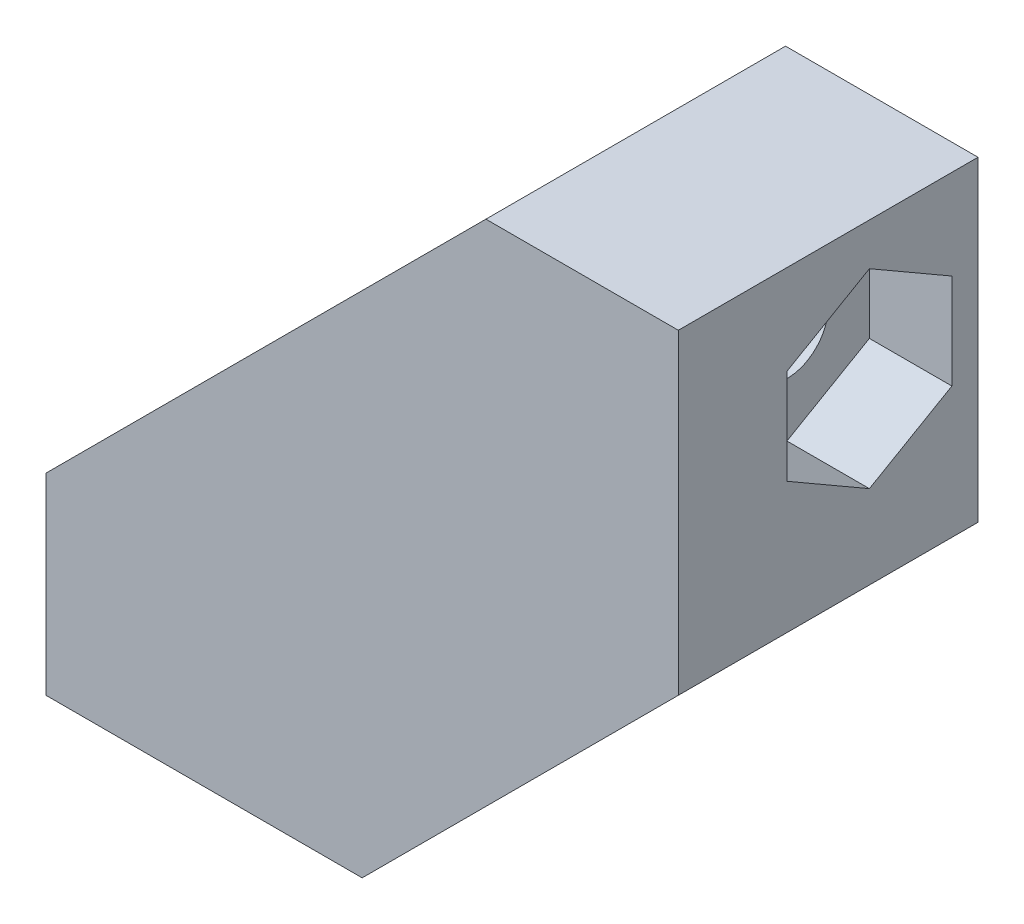
SolidWorks part; units mm, degrees
ref_plane "Front Plane" through (0, 0, 0) normal (0, 0, 1) x (1, 0, 0)
ref_plane "Top Plane" through (0, 0, 0) normal (0, 1, 0) x (1, 0, 0)
ref_plane "Right Plane" through (0, 0, 0) normal (1, 0, 0) x (0, 0, -1)
sketch "Sketch1" plane through (0, 0, 0) normal (0, 0, 1) x (1, 0, 0)
  line L0 (30, 0) -> (30, 6) construction
  line L2 (30, 0) -> (30, 8)
  line L3 (30, 8) -> (38, 8)
  line L5 (27, 0) -> (27, 6) construction
  line L6 (30, 0) -> (22, 0)
  line L8 (45, -7) -> (22, -7)
  line L9 (22, 0) -> (22, -7)
  line L11 (38, 8) -> (38, 16)
  line L12 (38, 16) -> (45, 16)
  line L13 (45, -7) -> (45, 16)
  line L14 (30, 6) -> (0, 6) construction
  line L15 (0, 0) -> (30, 0) construction
  line L16 (33.5, -7) -> (45, 4.5)
  dimension "D1" = 7
  dimension "D2" = 5
extrude "Boss-Extrude1" add sketch "Sketch1" against normal up to surface (7.9 mm away) contours L8 L16 L13 L12 L11 L3 L2 L6 L9
sketch "Sketch2" plane through (0, -7, 0) normal (0, -1, 0) x (1, 0, 0)
  circle A0 centre (27, -3.95) radius 1.5
  circle A1 centre (27, -3.95) radius 1.5 construction
extrude "Cut-Extrude1" cut sketch "Sketch2" against normal through all
sketch "Sketch3" plane through (38, -7, 0) normal (0, 1, 0) x (0, 0, -1)
  line L0 (0.95, 12.7321) -> (3.95, 14.4641)
  line L1 (3.95, 14.4641) -> (6.95, 12.7321)
  line L2 (6.95, 12.7321) -> (6.95, 9.2679)
  line L3 (6.95, 9.2679) -> (3.95, 7.5359)
  line L4 (3.95, 7.5359) -> (0.95, 9.2679)
  line L5 (0.95, 9.2679) -> (0.95, 12.7321)
  circle A0 centre (3.95, 11) radius 3.4641 construction
  circle A1 centre (3.95, 11) radius 1.5 construction
  dimension "D1" = 6
extrude "Cut-Extrude3" cut sketch "Sketch3" along normal blind 3
ref_plane "Plane1" through (19, 19, 0) normal (0.7071, 0.7071, 0) x (0.7071, -0.7071, 0)
sketch "Sketch4" plane through (0, 0, 0) normal (0, 0, 1) x (1, 0, 0)
  line L0 (22, 0) -> (38, 16)
  line L9 (22, -7) -> (33.5, -7)
  line L10 (33.5, -7) -> (45, 4.5)
  line L11 (45, 4.5) -> (45, 16)
  line L12 (45, 16) -> (38, 16)
  line L13 (38, 16) -> (38, 8)
  line L14 (38, 8) -> (30, 8)
  line L15 (30, 8) -> (30, 0)
  line L16 (30, 0) -> (22, 0)
  line L17 (22, 0) -> (22, -7)
  line L18 (22, -7) -> (33.5, -7)
  line L19 (33.5, -7) -> (45, 4.5)
  line L20 (45, 4.5) -> (45, 16)
  line L21 (45, 16) -> (38, 16)
  line L26 (22, 0) -> (22, -7)
  dimension "D1" = 0
extrude "Boss-Extrude2" add sketch "Sketch4" along normal blind 3
sketch "Sketch5" plane through (0, 0, 0) normal (0, 1, 0) x (1, 0, 0)
  line L1 (22, 8.2) -> (30.3048, 8.2)
  line L2 (22, 8.2) -> (22, -0.3)
  line L3 (22, -0.3) -> (30.3048, -0.3)
  line L4 (30.3048, 8.2) -> (30.3048, -0.3)
  line L6 (22, 7.9) -> (22, 0) construction
  line L7 (30, 7.9) -> (30, 0) construction
  line L8 (30, 3.95) -> (30.3048, 3.95) construction
  line L9 (30, 0) -> (22, 0) construction
  dimension "D1" = 0.3
  dimension "D2" = 0.3048
extrude "Cut-Extrude4" cut sketch "Sketch5" along normal through all
mirror "Mirror1" about plane through (19, 19, 0) normal (0.7071, 0.7071, 0) of "Cut-Extrude4", "Cut-Extrude1", "Cut-Extrude3"
chamfer "Chamfer1" distance 2 angle 57 2 edges at (34.1524, 7.6952, -7.9) (30.3048, 3.8476, -7.9)
